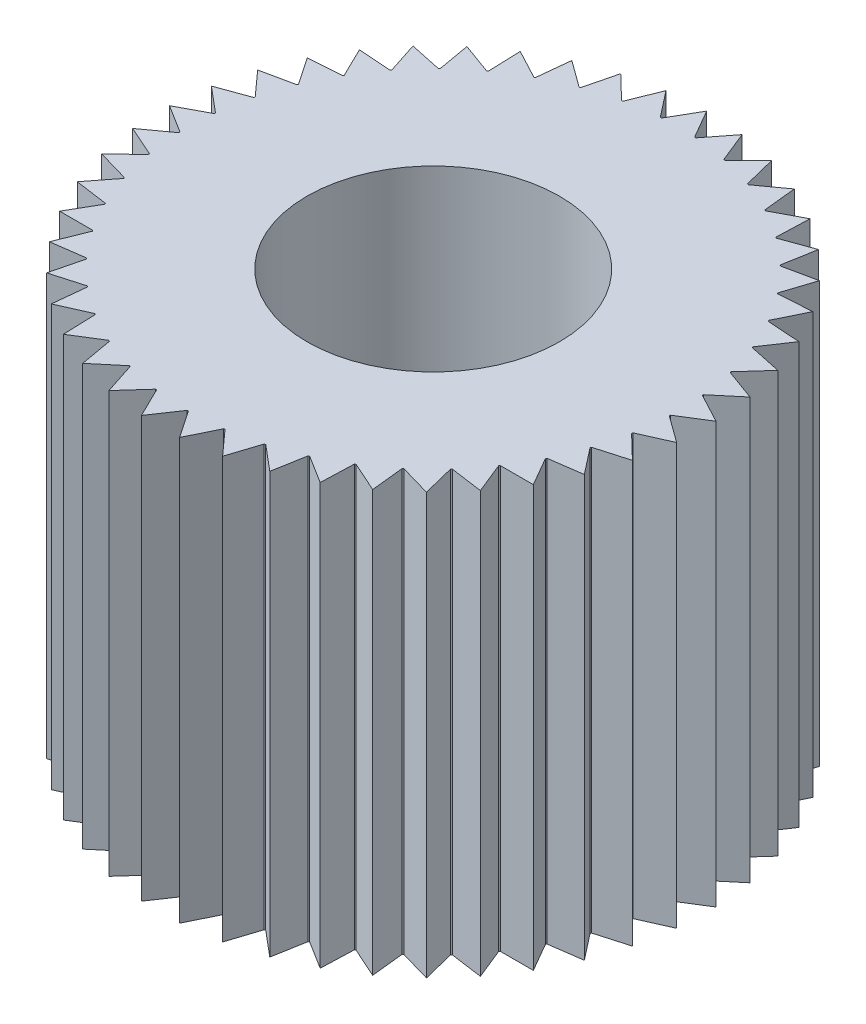
SolidWorks part; units mm, degrees
ref_plane "Front Plane" through (0, 0, 0) normal (0, 0, 1) x (1, 0, 0)
ref_plane "Top Plane" through (0, 0, 0) normal (0, 1, 0) x (1, 0, 0)
ref_plane "Right Plane" through (0, 0, 0) normal (1, 0, 0) x (0, 0, -1)
sketch "Sketch2" plane through (0, 0, 0) normal (0, 1, 0) x (1, 0, 0)
  line L0 (0.3447, 2.4524) -> (0.1605, 2.2167)
  line L1 (0, 2.4765) -> (-0.1496, 2.2175)
  line L2 (0.4567, 2.1751) -> (0.3447, 2.4524)
  line L3 (0.1496, 2.2175) -> (0, 2.4765)
  line L4 (0.6826, 2.3806) -> (0.4675, 2.1728)
  line L5 (0.755, 2.0903) -> (0.6826, 2.3806)
  line L6 (1.0073, 2.2624) -> (0.7653, 2.0866)
  line L7 (1.0385, 1.9649) -> (1.0073, 2.2624)
  line L8 (1.3123, 2.1002) -> (1.0482, 1.9598)
  line L9 (1.3019, 1.8013) -> (1.3123, 2.1002)
  line L10 (1.5919, 1.8971) -> (1.3108, 1.7948)
  line L11 (1.5399, 1.6025) -> (1.5919, 1.8971)
  line L12 (1.8404, 1.6571) -> (1.5478, 1.5949)
  line L13 (1.748, 1.3726) -> (1.8404, 1.6571)
  line L14 (2.0531, 1.3848) -> (1.7547, 1.364)
  line L15 (1.922, 1.116) -> (2.0531, 1.3848)
  line L16 (2.2259, 1.0856) -> (1.9275, 1.1065)
  line L17 (2.0586, 0.8377) -> (2.2259, 1.0856)
  line L18 (2.3553, 0.7653) -> (2.0627, 0.8275)
  line L19 (2.1551, 0.543) -> (2.3553, 0.7653)
  line L20 (2.4389, 0.43) -> (2.1578, 0.5323)
  line L21 (2.2097, 0.2378) -> (2.4389, 0.43)
  line L22 (2.475, 0.0864) -> (2.2109, 0.2269)
  line L23 (2.2213, -0.0721) -> (2.475, 0.0864)
  line L24 (2.4629, -0.2589) -> (2.2209, -0.0831)
  line L25 (2.1897, -0.3805) -> (2.4629, -0.2589)
  line L26 (2.4029, -0.5991) -> (2.1878, -0.3913)
  line L27 (2.1154, -0.6816) -> (2.4029, -0.5991)
  line L28 (2.2962, -0.9277) -> (2.112, -0.692)
  line L29 (2, -0.9693) -> (2.2962, -0.9277)
  line L30 (2.1447, -1.2382) -> (1.9952, -0.9792)
  line L31 (1.8456, -1.2382) -> (2.1447, -1.2382)
  line L32 (1.9515, -1.5247) -> (1.8395, -1.2474)
  line L33 (1.6553, -1.4831) -> (1.9515, -1.5247)
  line L34 (1.7203, -1.7814) -> (1.648, -1.4912)
  line L35 (1.4328, -1.699) -> (1.7203, -1.7814)
  line L36 (1.4557, -2.0035) -> (1.4244, -1.7061)
  line L37 (1.1824, -1.8819) -> (1.4557, -2.0035)
  line L38 (1.1626, -2.1866) -> (1.1731, -1.8877)
  line L39 (0.909, -2.0281) -> (1.1626, -2.1866)
  line L40 (0.847, -2.3271) -> (0.899, -2.0326)
  line L41 (0.6179, -2.1349) -> (0.847, -2.3271)
  line L42 (0.5149, -2.4224) -> (0.6073, -2.1379)
  line L43 (0.3147, -2.2001) -> (0.5149, -2.4224)
  line L44 (0.1728, -2.4705) -> (0.3039, -2.2016)
  line L46 (0.0055, -2.2225) -> (0.1728, -2.4705)
  line L47 (-0.1728, -2.4705) -> (-0.0055, -2.2225)
  line L48 (-0.3039, -2.2016) -> (-0.1728, -2.4705)
  line L49 (-0.5149, -2.4224) -> (-0.3147, -2.2001)
  line L50 (-0.6073, -2.1379) -> (-0.5149, -2.4224)
  line L51 (-0.847, -2.3271) -> (-0.6179, -2.1349)
  line L52 (-0.899, -2.0326) -> (-0.847, -2.3271)
  line L53 (-1.1626, -2.1866) -> (-0.909, -2.0281)
  line L54 (-1.1731, -1.8877) -> (-1.1626, -2.1866)
  line L55 (-1.4557, -2.0035) -> (-1.1824, -1.8819)
  line L56 (-1.4244, -1.7061) -> (-1.4557, -2.0035)
  line L57 (-1.7203, -1.7814) -> (-1.4328, -1.699)
  line L58 (-1.648, -1.4912) -> (-1.7203, -1.7814)
  line L59 (-1.9515, -1.5247) -> (-1.6553, -1.4831)
  line L60 (-1.8395, -1.2474) -> (-1.9515, -1.5247)
  line L61 (-2.1447, -1.2383) -> (-1.8456, -1.2383)
  line L62 (-1.9952, -0.9792) -> (-2.1447, -1.2383)
  line L63 (-2.2962, -0.9277) -> (-2, -0.9693)
  line L64 (-2.112, -0.692) -> (-2.2962, -0.9277)
  line L65 (-2.4029, -0.5991) -> (-2.1154, -0.6816)
  line L66 (-2.1878, -0.3913) -> (-2.4029, -0.5991)
  line L67 (-2.4629, -0.2589) -> (-2.1897, -0.3805)
  line L68 (-2.2209, -0.0831) -> (-2.4629, -0.2589)
  line L69 (-2.475, 0.0864) -> (-2.2213, -0.0721)
  line L70 (-2.2109, 0.2269) -> (-2.475, 0.0864)
  line L71 (-2.4389, 0.43) -> (-2.2097, 0.2378)
  line L72 (-2.1578, 0.5323) -> (-2.4389, 0.43)
  line L73 (-2.3553, 0.7653) -> (-2.1551, 0.543)
  line L74 (-2.0627, 0.8275) -> (-2.3553, 0.7653)
  line L75 (-2.2259, 1.0856) -> (-2.0586, 0.8377)
  line L76 (-1.9275, 1.1065) -> (-2.2259, 1.0856)
  line L77 (-2.0531, 1.3848) -> (-1.922, 1.116)
  line L78 (-1.7547, 1.364) -> (-2.0531, 1.3848)
  line L79 (-1.8404, 1.6571) -> (-1.748, 1.3726)
  line L80 (-1.5478, 1.5949) -> (-1.8404, 1.6571)
  line L81 (-1.5919, 1.8971) -> (-1.5399, 1.6025)
  line L82 (-1.3108, 1.7948) -> (-1.5919, 1.8971)
  line L83 (-1.3123, 2.1002) -> (-1.3019, 1.8013)
  line L84 (-1.0482, 1.9598) -> (-1.3123, 2.1002)
  line L85 (-1.0073, 2.2624) -> (-1.0385, 1.9649)
  line L86 (-0.7653, 2.0866) -> (-1.0073, 2.2624)
  line L87 (-0.6826, 2.3806) -> (-0.755, 2.0903)
  line L88 (-0.4675, 2.1728) -> (-0.6826, 2.3806)
  line L89 (-0.3447, 2.4524) -> (-0.4567, 2.1751)
  line L90 (-0.1605, 2.2167) -> (-0.3447, 2.4524)
  arc A0 (-0.1496, 2.2175) -> (-0.1605, 2.2167) centre (0, 0) ccw
  circle A1 centre (0, 2.2225) radius 0.127 construction
  arc A2 (0.1605, 2.2167) -> (0.1496, 2.2175) centre (0, 0) ccw
  arc A3 (0.4675, 2.1728) -> (0.4567, 2.1751) centre (0, 0) ccw
  arc A4 (0.7653, 2.0866) -> (0.755, 2.0903) centre (0, 0) ccw
  arc A5 (1.0482, 1.9598) -> (1.0385, 1.9649) centre (0, 0) ccw
  arc A6 (1.3108, 1.7948) -> (1.3019, 1.8013) centre (0, 0) ccw
  arc A7 (1.5478, 1.5949) -> (1.5399, 1.6025) centre (0, 0) ccw
  arc A8 (1.7547, 1.364) -> (1.748, 1.3726) centre (0, 0) ccw
  arc A9 (1.9275, 1.1065) -> (1.922, 1.116) centre (0, 0) ccw
  arc A10 (-0.4567, 2.1751) -> (-0.4675, 2.1728) centre (0, 0) ccw
  arc A11 (-0.755, 2.0903) -> (-0.7653, 2.0866) centre (0, 0) ccw
  arc A12 (-1.0385, 1.9649) -> (-1.0482, 1.9598) centre (0, 0) ccw
  arc A13 (-1.3019, 1.8013) -> (-1.3108, 1.7948) centre (0, 0) ccw
  arc A14 (-1.5399, 1.6025) -> (-1.5478, 1.5949) centre (0, 0) ccw
  arc A15 (-1.748, 1.3726) -> (-1.7547, 1.364) centre (0, 0) ccw
  arc A16 (-1.922, 1.116) -> (-1.9275, 1.1065) centre (0, 0) ccw
  arc A17 (-2.0586, 0.8377) -> (-2.0627, 0.8275) centre (0, 0) ccw
  arc A18 (-2.1551, 0.543) -> (-2.1578, 0.5323) centre (0, 0) ccw
  arc A19 (-2.2097, 0.2378) -> (-2.2109, 0.2269) centre (0, 0) ccw
  arc A20 (-2.2213, -0.0721) -> (-2.2209, -0.0831) centre (0, 0) ccw
  arc A21 (2.0627, 0.8275) -> (2.0586, 0.8377) centre (0, 0) ccw
  arc A22 (2.1578, 0.5323) -> (2.1551, 0.543) centre (0, 0) ccw
  arc A23 (2.2109, 0.2269) -> (2.2097, 0.2378) centre (0, 0) ccw
  arc A24 (2.2209, -0.0831) -> (2.2213, -0.0721) centre (0, 0) ccw
  arc A25 (2.1878, -0.3913) -> (2.1897, -0.3805) centre (0, 0) ccw
  arc A26 (2.112, -0.692) -> (2.1154, -0.6816) centre (0, 0) ccw
  arc A27 (1.9952, -0.9792) -> (2, -0.9693) centre (0, 0) ccw
  arc A28 (1.8395, -1.2474) -> (1.8456, -1.2382) centre (0, 0) ccw
  arc A29 (1.648, -1.4912) -> (1.6553, -1.4831) centre (0, 0) ccw
  arc A30 (1.4244, -1.7061) -> (1.4328, -1.699) centre (0, 0) ccw
  arc A31 (1.1731, -1.8877) -> (1.1824, -1.8819) centre (0, 0) ccw
  arc A32 (0.899, -2.0326) -> (0.909, -2.0281) centre (0, 0) ccw
  arc A33 (0.6073, -2.1379) -> (0.6179, -2.1349) centre (0, 0) ccw
  arc A34 (0.3039, -2.2016) -> (0.3147, -2.2001) centre (0, 0) ccw
  arc A35 (-0.0055, -2.2225) -> (0.0055, -2.2225) centre (0, 0) ccw
  arc A36 (-0.3147, -2.2001) -> (-0.3039, -2.2016) centre (0, 0) ccw
  arc A37 (-0.6179, -2.1349) -> (-0.6073, -2.1379) centre (0, 0) ccw
  arc A38 (-0.909, -2.0281) -> (-0.899, -2.0326) centre (0, 0) ccw
  arc A39 (-1.1824, -1.8819) -> (-1.1731, -1.8877) centre (0, 0) ccw
  arc A40 (-1.4328, -1.699) -> (-1.4244, -1.7061) centre (0, 0) ccw
  arc A41 (-1.6553, -1.4831) -> (-1.648, -1.4912) centre (0, 0) ccw
  arc A42 (-1.8456, -1.2383) -> (-1.8395, -1.2474) centre (0, 0) ccw
  arc A43 (-2, -0.9693) -> (-1.9952, -0.9792) centre (0, 0) ccw
  arc A44 (-2.1154, -0.6816) -> (-2.112, -0.692) centre (0, 0) ccw
  arc A45 (-2.1897, -0.3805) -> (-2.1878, -0.3913) centre (0, 0) ccw
extrude "Boss-Extrude1" add sketch "Sketch2" along normal blind 3.81
sketch "Sketch4" plane through (0, 3.81, 0) normal (0, 1, 0) x (1, 0, 0)
  circle A0 centre (0, 0) radius 1.143
  dimension "D1" = 2.286
extrude "Cut-Extrude2" cut sketch "Sketch4" against normal blind 2.286
sketch "Sketch5" plane through (0, 0, 0) normal (0, -1, 0) x (1, 0, 0)
  circle A0 centre (0, 0) radius 0.635
  dimension "D1" = 1.27
extrude "Cut-Extrude3" cut sketch "Sketch5" against normal blind 1.27
